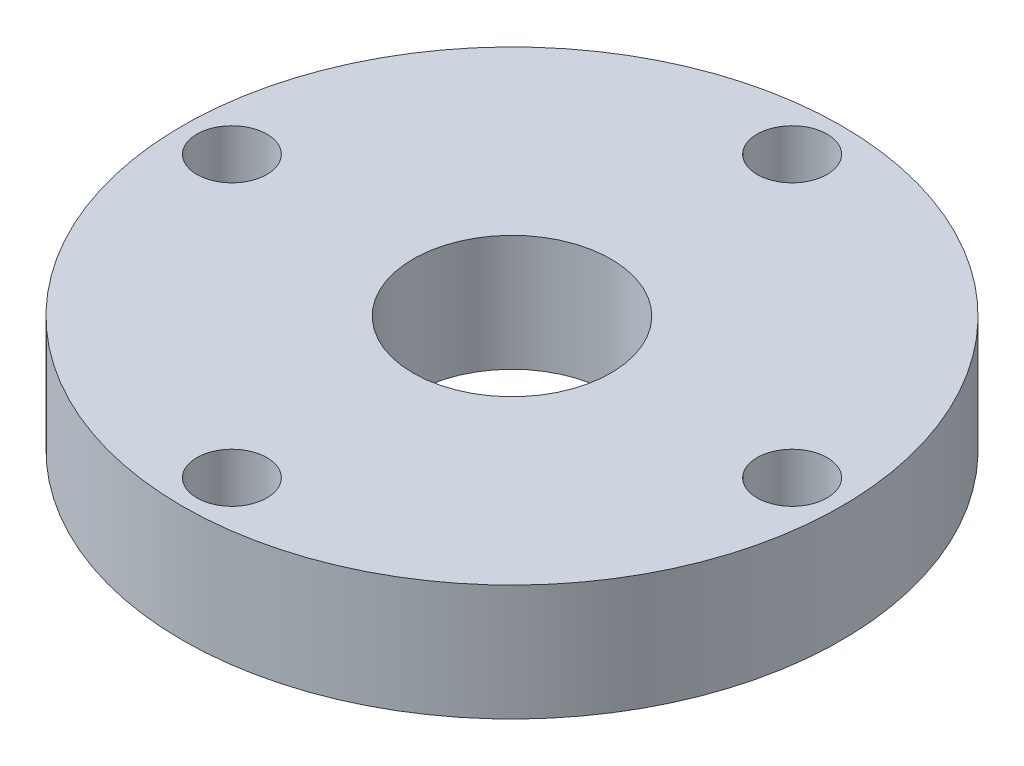
SolidWorks part; units mm, degrees
ref_plane "Front Plane" through (0, 0, 0) normal (1, 0, 0) x (0, 1, 0)
ref_plane "Top Plane" through (0, 0, 0) normal (0, 0, 1) x (0, 1, 0)
ref_plane "Right Plane" through (0, 0, 0) normal (0, 1, 0) x (-1, 0, 0)
sketch "Sketch1" plane through (0, 0, 0) normal (0, 0, 1) x (0, 1, 0)
  line L0 (-11.176, 0) -> (-11.176, 63.5)
  line L1 (-11.176, 63.5) -> (11.176, 63.5)
  line L2 (11.176, 63.5) -> (11.176, 0)
  line L3 (11.176, 0) -> (-11.176, 0)
  line L4 (-36.576, 0) -> (36.576, 0) construction
revolve "Revolve1" add sketch "Sketch1" angle 360 about L4
sketch "Sketch2" plane through (0, 0, 0) normal (0, 1, 0) x (-1, 0, 0)
  circle A0 centre (0, 0) radius 19.05
extrude "Cut-Extrude2" cut sketch "Sketch2" against normal through all from offset 11.176
hole_wizard "CBORE for 5/16 Socket Head Cap Screw1" positions "Sketch4" profile "Sketch3" counterbore size "5/16" standard "ANSI Inch"
sketch "Sketch4" plane through (0, 11.176, 0) normal (0, 1, 0) x (1, 0, 0)
  circle A0 centre (0, 0) radius 53.975 construction
  point P0 (-53.975, 0)
  point P1 (0, -53.975)
  point P3 (53.975, 0)
  point P5 (0, 53.975)
sketch "Sketch3" plane through (-53.975, 11.176, 0) normal (1, 0, 0) x (0, 0, 1)
  line L0 (0, 0) -> (0, 24.977)
  line L1 (0, 24.977) -> (4.3688, 22.352)
  line L2 (4.3688, 22.352) -> (4.3688, 9.652)
  line L3 (4.3688, 9.652) -> (6.7437, 9.652)
  line L4 (6.7437, 9.652) -> (6.7437, 0)
  line L5 (6.7437, 0) -> (0, 0)
  line L10 (0, 24.977) -> (-4.3688, 22.352) construction
  line L11 (0, -6.35) -> (0, 107.95) construction
  dimension "Hole Dia." = 8.7376
  dimension "Hole Depth" = 22.352
  dimension "C'Bore Dia." = 13.4874
  dimension "C'Bore Depth" = 9.652
  dimension "Drill Angle" = 118
